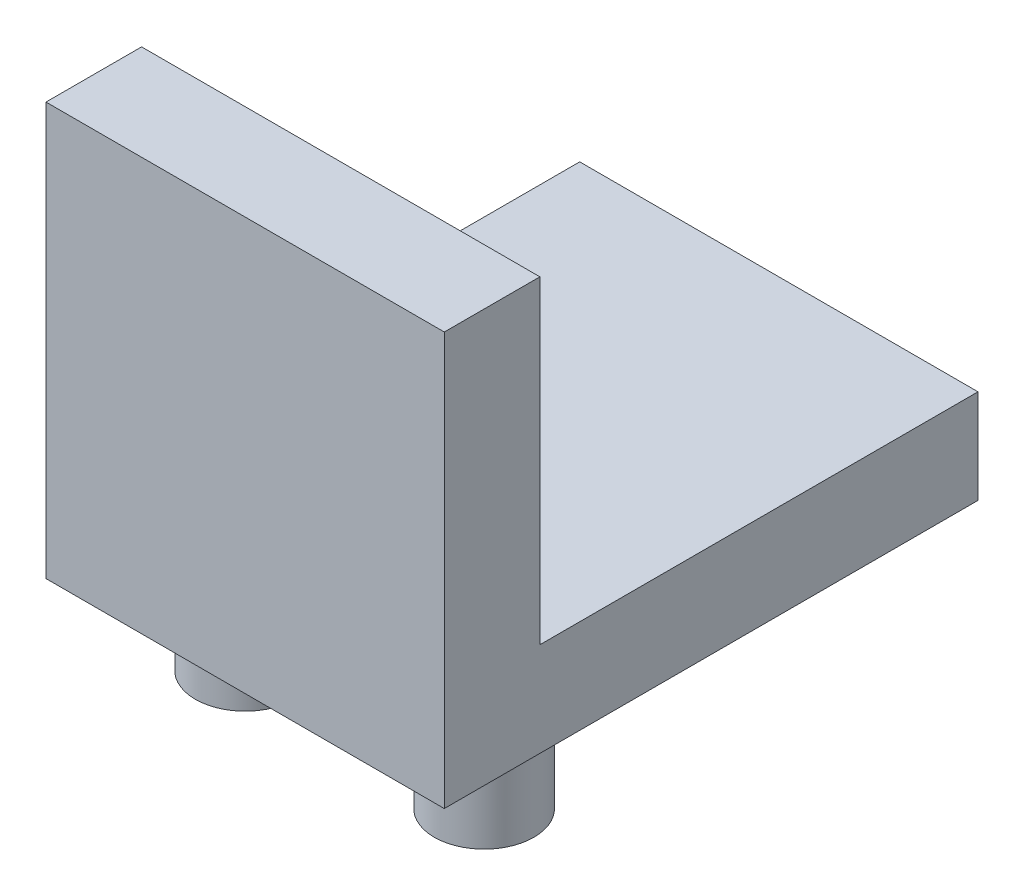
SolidWorks part; units mm, degrees
ref_plane "Front Plane" through (0, 0, 0) normal (0, 0, 1) x (1, 0, 0)
ref_plane "Top Plane" through (0, 0, 0) normal (0, 1, 0) x (1, 0, 0)
ref_plane "Right Plane" through (0, 0, 0) normal (1, 0, 0) x (0, 0, -1)
sketch "Sketch1" plane through (0, 0, 0) normal (0, 1, 0) x (1, 0, 0)
  line L0 (-6.35, 0.381) -> (6.35, 0.381)
  line L1 (-6.35, -3.429) -> (6.35, -3.429)
  line L2 (-6.35, -3.429) -> (-6.35, 3.429)
  line L3 (-6.35, 3.429) -> (6.35, 3.429)
  line L4 (6.35, -3.429) -> (6.35, 3.429)
  line L5 (-6.35, -3.429) -> (6.35, 3.429) construction
  line L6 (-6.35, 3.429) -> (6.35, -3.429) construction
  line L7 (0, 3.429) -> (0, -3.429) construction
  circle A0 centre (-3.81, 0.381) radius 1.5875
  circle A1 centre (3.81, 0.381) radius 1.5875
  point P0 (0, 0)
  dimension "D4" = 3.175
  dimension "D1" = 12.7
  dimension "D2" = 6.858
  dimension "D3" = 3.81
  dimension "D5" = 3.81
sketch "Sketch2" plane through (0, 0, 0) normal (0, 1, 0) x (1, 0, 0)
  line L4 (-6.35, -3.429) -> (6.35, -3.429)
  line L5 (6.35, -3.429) -> (6.35, 3.429)
  line L6 (6.35, 3.429) -> (-6.35, 3.429)
  line L7 (-6.35, 3.429) -> (-6.35, -3.429)
  line L8 (-6.35, -3.429) -> (6.35, -3.429)
  line L9 (6.35, -3.429) -> (6.35, 3.429)
  line L10 (6.35, 3.429) -> (-6.35, 3.429)
  line L11 (-6.35, 3.429) -> (-6.35, -3.429)
  dimension "D3" = 0
extrude "Boss-Extrude1" add sketch "Sketch2" along normal blind 3
sketch "Sketch3" plane through (0, 0, 0) normal (0, -1, 0) x (1, 0, 0)
  circle A0 centre (3.81, -0.381) radius 1.5875 construction
  circle A1 centre (-3.81, -0.381) radius 1.5875 construction
  circle A2 centre (3.81, -0.381) radius 1.5875
  circle A3 centre (-3.81, -0.381) radius 1.5875
extrude "Boss-Extrude2" add sketch "Sketch3" along normal blind 3.175
sketch "Sketch4" plane through (0, 3, 0) normal (0, 1, 0) x (1, 0, 0)
  line L0 (6.35, -3.429) -> (6.35, 3.429) construction
  line L5 (-6.35, -3.429) -> (6.35, -3.429)
  line L6 (-6.35, -3.429) -> (-6.35, 0.381)
  line L7 (-6.35, 0.381) -> (6.35, 0.381)
  line L8 (6.35, -3.429) -> (6.35, 0.381)
  dimension "D1" = 3.81
extrude "Boss-Extrude3" add sketch "Sketch4" along normal blind 10.16
sketch "Sketch8" plane through (0, 0, -3.429) normal (0, 0, -1) x (-1, 0, 0)
  line L4 (-6.35, 0) -> (6.35, 0)
  line L5 (6.35, 0) -> (6.35, 3)
  line L6 (6.35, 3) -> (-6.35, 3)
  line L7 (-6.35, 3) -> (-6.35, 0)
  line L8 (-6.35, 0) -> (6.35, 0)
  line L9 (6.35, 0) -> (6.35, 3)
  line L10 (6.35, 3) -> (-6.35, 3)
  line L11 (-6.35, 3) -> (-6.35, 0)
  dimension "D1" = 0
extrude "Boss-Extrude6" add sketch "Sketch8" along normal blind 10.16
sketch "Sketch11" plane through (0, 0, 0) normal (0, -1, 0) x (1, 0, 0)
  line L0 (0, -0.381) -> (0, -8.001) construction
  line L1 (-6.35, 3.429) -> (6.35, 3.429)
  line L2 (-6.35, 3.429) -> (-6.35, -0.381)
  line L3 (-6.35, -0.381) -> (6.35, -0.381)
  line L4 (6.35, 3.429) -> (6.35, -0.381)
  circle A0 centre (0, -8.001) radius 1.5875
  dimension "D1" = 7.62
extrude "Boss-Extrude7" add sketch "Sketch11" along normal blind 3.175
sketch "Sketch12" plane through (0, 13.16, 0) normal (0, 1, 0) x (1, 0, 0)
  line L0 (6.35, -3.429) -> (6.35, 0.381) construction
  line L1 (-6.35, -3.429) -> (6.35, -3.429)
  line L2 (-6.35, -3.429) -> (-6.35, -0.381)
  line L3 (-6.35, -0.381) -> (6.35, -0.381)
  line L4 (6.35, -3.429) -> (6.35, -0.381)
  line L6 (-6.35, 0.381) -> (6.35, 0.381)
  line L7 (-6.35, 0.381) -> (-6.35, -0.381)
  line L8 (-6.35, -0.381) -> (6.35, -0.381)
  line L9 (6.35, 0.381) -> (6.35, -0.381)
  line M2 (-6.35, 0.381) -> (-6.35, -3.429)
  line M4 (6.35, -3.429) -> (6.35, 0.381)
  line M5 (6.35, 0.381) -> (-6.35, 0.381)
  dimension "D1" = 3.048
extrude "Cut-Extrude1" cut sketch "Sketch12" along direction (0, 1, 0) on the side against the normal up to surface (10.16 mm away) contours L3 M2 M4 M5
